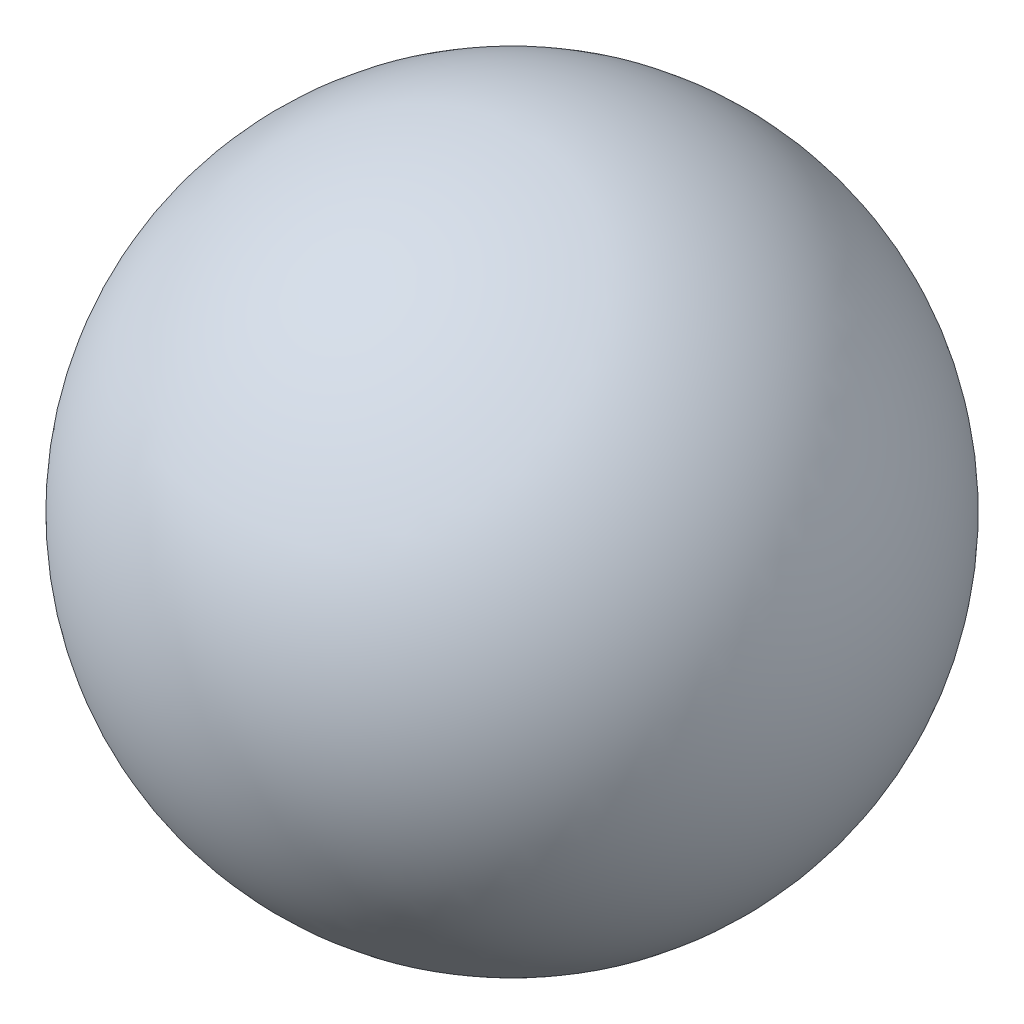
SolidWorks part; units mm, degrees
ref_plane "前视基准面" through (0, 0, 0) normal (0, 0, 1) x (1, 0, 0)
ref_plane "上视基准面" through (0, 0, 0) normal (0, 1, 0) x (1, 0, 0)
ref_plane "右视基准面" through (0, 0, 0) normal (1, 0, 0) x (0, 0, -1)
other "Configuration Table"
sketch "草图1" plane through (0, 0, 0) normal (0, 0, 1) x (1, 0, 0)
  line L0 (0, 123) -> (0, -123)
  line L1 (0, -123) -> (-0.3799, -123.9238)
  arc A0 (0, -123) -> (0, 123) centre (0, 0) ccw
  dimension "D1" = 246
revolve "旋转1" add sketch "草图1" angle 360 about L0
